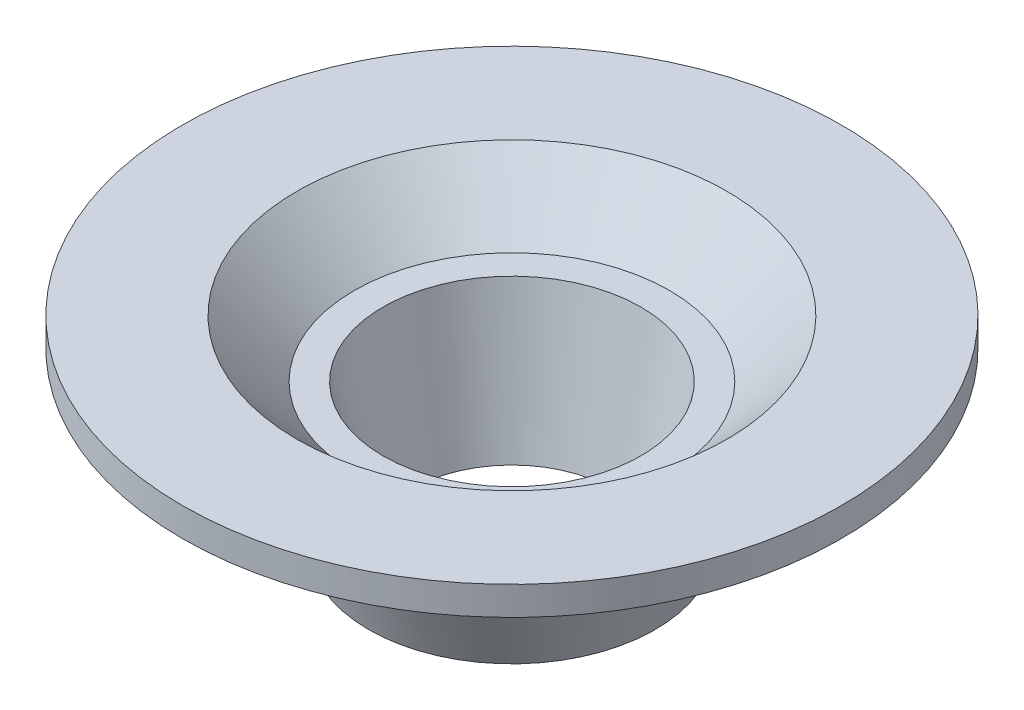
SolidWorks part; units mm, degrees
ref_plane "Ebene vorne" through (0, 0, 0) normal (0, 0, 1) x (1, 0, 0)
ref_plane "Ebene oben" through (0, 0, 0) normal (0, 1, 0) x (1, 0, 0)
ref_plane "Ebene rechts" through (0, 0, 0) normal (1, 0, 0) x (0, 0, -1)
sketch "Sketch1" plane through (0, 0, 0) normal (1, 0, 0) x (0, 0, -1)
  line L0 (0, 0) -> (0, -2.2643) construction
  line L1 (3.5, -5) -> (4.5, 0)
  line L2 (4.5, 0) -> (5.5, 0)
  line L3 (5.5, 0) -> (7.5, 2)
  line L4 (7.5, 2) -> (11.5, 2)
  line L5 (11.5, 2) -> (11.5, 1)
  line L6 (11.5, 1) -> (9.5, 1)
  line L7 (9.5, 1) -> (7.5, -1)
  line L8 (7.5, -1) -> (6.5, -1)
  line L9 (6.5, -1) -> (5, -5)
  line L10 (5, -5) -> (3.5, -5)
  point P5 (0, 0)
  point P14 (0, 0)
  point P15 (4.0096, 0)
  point P16 (5.5773, 0)
  point P17 (7.5, -1)
  point P18 (9.874, 1)
  dimension "D1" = 1.5
  dimension "D2" = 5
  dimension "D3" = 3.5
  dimension "D4" = 4.5
  dimension "D5" = 2
  dimension "D6" = 2
  dimension "D7" = 1
  dimension "D8" = 4
  dimension "D9" = 2
  dimension "D10" = 1
  dimension "D11" = 6.5
  dimension "D12" = 1
revolve "Revolve1" add sketch "Sketch1" angle 360 about L0
